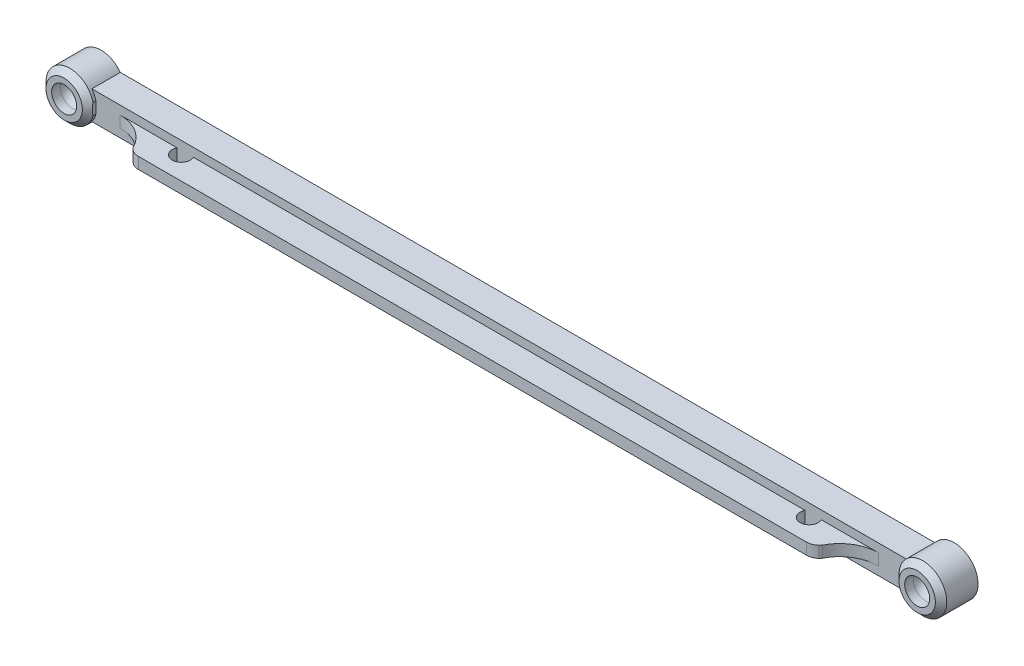
SolidWorks part; units mm, degrees
ref_plane "정면" through (0, 0, 0) normal (0, 0, 1) x (1, 0, 0)
ref_plane "윗면" through (0, 0, 0) normal (0, 1, 0) x (1, 0, 0)
ref_plane "우측면" through (0, 0, 0) normal (1, 0, 0) x (0, 0, -1)
sketch "스케치1" plane through (0, 0, 0) normal (1, 0, 0) x (0, 0, -1)
  line L0 (0, 2.5) -> (0, 6.7)
  line L1 (8.9614, 2.5) -> (-8.9614, 2.5) construction
  line L2 (0, 6.7) -> (-5.5, 6.7)
  line L3 (-5.5, 6.7) -> (-6.5002, 5.6981)
  line L4 (-6.5002, 5.6981) -> (-6.5002, 4.6981)
  line L5 (-4.8735, 2.5013) -> (-4.8735, 2.5)
  line L6 (-6.5002, 4.6981) -> (-5.0002, 4.6981)
  line L7 (-3.01, 2.5) -> (0, 2.5)
  arc A0 (-5.0002, 4.6981) -> (-3.01, 2.5) centre (-5.0002, 2.6981) cw
  dimension "D9" = 2
  dimension "D1" = 2.5
  dimension "D2" = 4.2
  dimension "D3" = 5.5
  dimension "D4" = 1.4157
  dimension "D5" = 1
  dimension "D6" = 134.95
  dimension "D8" = 1.5
ref_plane "평면1" through (150, 0, 0) normal (1, 0, 0) x (0, 0, -1)
ref_plane "평면2" through (75, 0, 0) normal (1, 0, 0) x (0, 0, -1)
sketch "스케치2" plane through (150, 0, 0) normal (1, 0, 0) x (0, 0, -1)
  line L0 (-8.9614, 2.5) -> (0, 2.5) construction
  line L1 (0, 2.5) -> (0, 6.7)
  line L2 (0, 6.7) -> (-5.5, 6.7)
  line L3 (-5.5, 6.7) -> (-6.5002, 5.6981)
  line L4 (-6.5002, 5.6981) -> (-6.5002, 4.6981)
  line L5 (-6.5002, 4.6981) -> (-5.0002, 4.6981)
  line L6 (-3.01, 2.5) -> (0, 2.5)
  arc A0 (-3.01, 2.5) -> (-5.0002, 4.6981) centre (-5.0002, 2.6981) ccw
revolve "회전2" add sketch "스케치1" angle 360 about L1
revolve "회전3" add sketch "스케치2" angle 360 about L6
sketch "스케치3" plane through (75, 0, 0) normal (1, 0, 0) x (0, 0, -1)
  line L0 (-5, 3.5) -> (-5, 5)
  line L1 (0, 0) -> (-5, 0)
  line L2 (0, 0) -> (0, 5)
  line L3 (0, 5) -> (-5, 5)
  line L4 (-5, 0) -> (-5, 1.5)
  line L5 (-5, 3.5) -> (-9.7, 3.5)
  line L7 (-5, 1.5) -> (-9.7, 1.5)
  line L8 (-9.7, 3.5) -> (-9.7, 1.5)
  dimension "D1" = 5
  dimension "D2" = 5
  dimension "D3" = 1.5
  dimension "D4" = 1.5
  dimension "D5" = 4.7
extrude "보스-돌출1" add sketch "스케치3" along normal up to surface and the other way up to surface up to face at (150, -1.7, 5.5) other way up to face at (0, 6.7, 5.5)
sketch "스케치4" plane through (0, 1.5, 0) normal (0, -1, 0) x (1, 0, 0)
  line L0 (145.9208, 9.7) -> (4.0792, 9.7) construction
  line L1 (75, 9.7) -> (16.27, 9.7)
  line L2 (133.73, 9.7) -> (133.73, 5)
  line L3 (75, 5) -> (16.27, 5)
  line L4 (16.27, 9.7) -> (16.27, 5)
  line L5 (145.9208, 5) -> (4.0792, 5) construction
  line L6 (16.27, 9.7) -> (14.6696, 9.0699)
  line L7 (14.6696, 9.0699) -> (14.4321, 8.8128)
  line L8 (14.4321, 8.8128) -> (8.1591, 5.0017)
  line L9 (16.27, 5) -> (4.0792, 5)
  line L10 (16.27, 9.7) -> (4.0792, 9.7)
  line L11 (4.0792, 9.7) -> (4.0792, 5)
  line L12 (133.73, 5) -> (145.9208, 5)
  line L13 (145.9208, 9.7) -> (145.9208, 5)
  line L14 (133.73, 9.7) -> (145.9208, 9.7)
  line L15 (135.3304, 9.0699) -> (135.5679, 8.8128)
  line L19 (75, 20.1941) -> (75, -11.4942) construction
  arc A0 (16.27, 9.7) -> (14.6696, 9.0699) centre (16.27, 7.3524) ccw
  arc A1 (8.1591, 5.0017) -> (14.4321, 8.8128) centre (8.3104, 11.8209) ccw
  arc A2 (141.8409, 5.0017) -> (135.5679, 8.8128) centre (141.6896, 11.8209) cw
  arc A3 (133.73, 9.7) -> (135.3304, 9.0699) centre (133.73, 7.3524) cw
  dimension "D4" = 0.35
  dimension "D1" = 58.73
  dimension "D2" = 1.72
  dimension "D3" = 68.51
  dimension "D5" = 154.21
  dimension "D6" = 7.34
  dimension "D7" = 164
extrude "컷-돌출2" cut sketch "스케치4" against normal through all
sketch "스케치6" plane through (0, 1.5, 0) normal (0, -1, 0) x (1, 0, 0)
  line L1 (75, 9.7) -> (75, 5) construction
  line L2 (18.356, 5) -> (21.233, 5)
  line L3 (131.644, 5) -> (128.767, 5)
  line L4 (16.27, 17.6517) -> (16.27, -9.3177) construction
  arc A0 (18.356, 5) -> (21.233, 5) centre (19.7945, 5.7005) cw
  arc A1 (131.644, 5) -> (128.767, 5) centre (130.2055, 5.7005) ccw
  point P8 (18.356, 5)
  point P9 (21.233, 5)
  line M10 (8.3104, 5) -> (141.6896, 5)
  dimension "D1" = 2.086
  dimension "D2" = 2.877
extrude "컷-돌출3" cut sketch "스케치6" against normal through all contours A0 M10 | A1 M10
